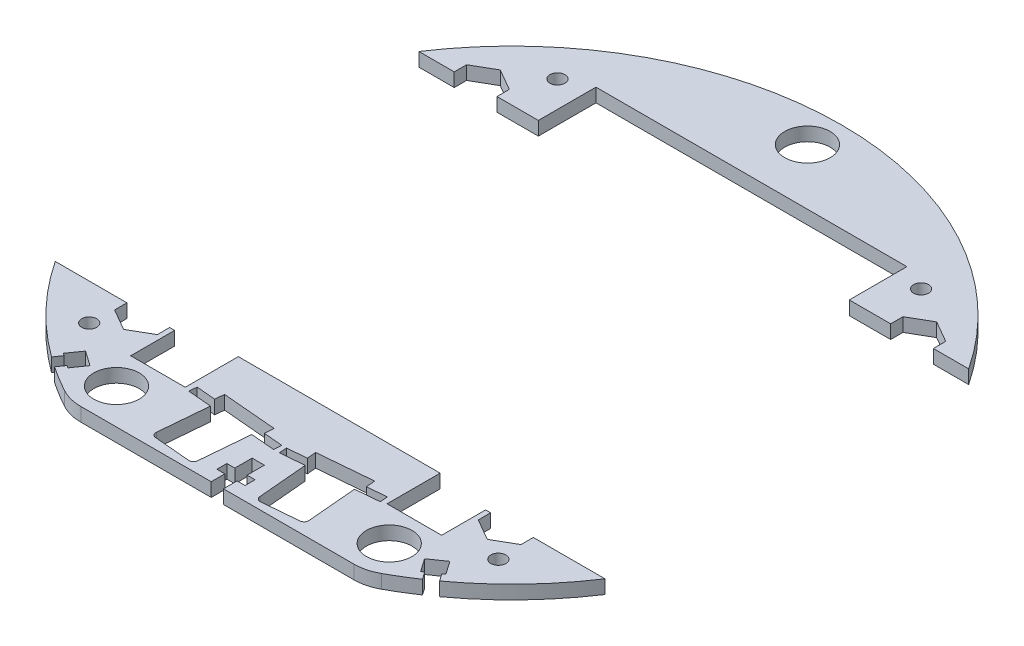
SolidWorks part; units mm, degrees
ref_plane "Front Plane" through (0, 0, 0) normal (0, 0, 1) x (1, 0, 0)
ref_plane "Top Plane" through (0, 0, 0) normal (0, 1, 0) x (1, 0, 0)
ref_plane "Right Plane" through (0, 0, 0) normal (1, 0, 0) x (0, 0, -1)
sketch "Sketch1" plane through (0, 0, 0) normal (0, 1, 0) x (1, 0, 0)
  line L0 (-30.03, -64.8129) -> (30.03, -64.8129)
  line L1 (0, -85) -> (0, 0) construction
  line L2 (0, -85) -> (32.4891, -64.8129) construction
  arc A0 (34.8348, -63.5829) -> (-34.8348, -63.5829) centre (0, 0) ccw
  circle A1 centre (0, -85) radius 38.25 construction
  arc A2 (30.03, -64.8129) -> (34.8348, -63.5829) centre (30.03, -54.8129) ccw
  arc A3 (-30.03, -64.8129) -> (-34.8348, -63.5829) centre (-30.03, -54.8129) cw
  dimension "D1" = 145
  dimension "D2" = 76.5
  dimension "D4" = 10
  dimension "D3" = 85
extrude "Boss-Extrude1" add sketch "Sketch1" along normal blind 3
sketch "Sketch2" plane through (0, 3, 0) normal (0, 1, 0) x (1, 0, 0)
  line L29 (-22.2, -49.6757) -> (-22.2, -32.5) construction
  line L30 (-22.2, -49.6757) -> (-22.2, -32.5) construction
  line L38 (-34.2, -49.6757) -> (-22.2, -49.6757) construction
  line L39 (-34.2, -49.6757) -> (-34.2, 49.6757) construction
  line L40 (-34.2, 49.6757) -> (-22.2, 49.6757) construction
  line L41 (-22.2, 32.5) -> (-22.2, 49.6757) construction
  line L47 (22.2, 32.5) -> (22.2, 49.6757) construction
  line L48 (34.2, 49.6757) -> (22.2, 49.6757) construction
  line L49 (34.2, -49.6757) -> (34.2, 49.6757) construction
  line L50 (34.2, -49.6757) -> (22.2, -49.6757) construction
  line L51 (22.2, -49.6757) -> (22.2, -32.5) construction
  line L52 (22.2, -49.6757) -> (22.2, -32.5) construction
  line L53 (-22.2, -49.6757) -> (-22.2, -38) construction
  line L54 (-22.2, -49.6757) -> (-22.2, -38)
  line L55 (-22.2, 44) -> (22.2, 44)
  line L62 (-34.2, -49.6757) -> (-22.2, -49.6757)
  line L63 (-34.2, -49.6757) -> (-34.2, 49.6757)
  line L64 (-34.2, 49.6757) -> (-22.2, 49.6757)
  line L65 (-22.2, 44) -> (-22.2, 49.6757)
  line L71 (22.2, 44) -> (22.2, 49.6757)
  line L72 (34.2, 49.6757) -> (22.2, 49.6757)
  line L73 (34.2, -49.6757) -> (34.2, 49.6757)
  line L74 (34.2, -49.6757) -> (22.2, -49.6757)
  line L75 (22.2, -49.6757) -> (22.2, -38) construction
  line L76 (22.2, -49.6757) -> (22.2, -38)
  line L77 (-22.2, -38) -> (22.2, -38)
  dimension "D1" = 38
  dimension "D2" = 44
extrude "Cut-Extrude1" cut sketch "Sketch2" against normal through all
sketch "Sketch3" plane through (0, 3, 0) normal (0, 1, 0) x (1, 0, 0)
  line L0 (-34.2, 40) -> (-34.2, -40)
  line L1 (-72.5, -40) -> (-34.2, -40)
  line L2 (-72.5, -40) -> (-72.5, 40)
  line L3 (-72.5, 40) -> (-34.2, 40)
  line L4 (72.5, -40) -> (72.5, 40)
  line L5 (-72.5, -40) -> (72.5, 40) construction
  line L6 (-72.5, 40) -> (72.5, -40) construction
  line L8 (34.2, 40) -> (34.2, -40)
  line L10 (34.2, 40) -> (72.5, 40)
  line L11 (34.2, -40) -> (72.5, -40)
  line L12 (-34.2, -49.6757) -> (-34.2, 49.6757) construction
  line L13 (34.2, -49.6757) -> (34.2, 49.6757) construction
  arc A0 (34.8348, -63.5829) -> (-34.8348, -63.5829) centre (0, 0) ccw construction
  point P0 (0, 0)
  dimension "D1" = 80
extrude "Cut-Extrude2" cut sketch "Sketch3" against normal through all
sketch "Sketch4" plane through (0, 3, 0) normal (0, 1, 0) x (1, 0, 0)
  line L0 (-21.0702, -50.0262) -> (-0.6482, -51.8129)
  line L1 (21.0702, -50.0262) -> (20.922, -48.3326)
  line L2 (0.6482, -51.8129) -> (0.5, -50.1193)
  line L3 (20.922, -48.3326) -> (0.5, -50.1193)
  line L4 (0, 0) -> (0, -64.8129) construction
  line L5 (-30.03, -64.8129) -> (30.03, -64.8129) construction
  line L6 (-20.922, -48.3326) -> (-0.5, -50.1193)
  line L7 (-0.6482, -51.8129) -> (-0.5, -50.1193)
  line L8 (-21.0702, -50.0262) -> (-20.922, -48.3326)
  line L14 (21.0702, -50.0262) -> (0.6482, -51.8129)
  dimension "D1" = 1.7
  dimension "D2" = 20.5
  dimension "D3" = 5
  dimension "D4" = 13
  dimension "D5" = 0.5
extrude "Cut-Extrude3" cut sketch "Sketch4" against normal through all
sketch "Sketch5" plane through (0, 3, 0) normal (0, 1, 0) x (1, 0, 0)
  line L0 (5.8782, -51.3553) -> (15.8401, -50.4837)
  line L1 (5.8782, -51.3553) -> (6.8369, -62.3134)
  line L2 (15.8401, -50.4837) -> (16.7988, -61.4419)
  line L3 (7.9203, -63.2225) -> (15.8898, -62.5252)
  line L4 (0.6482, -51.8129) -> (21.0702, -50.0262) construction
  line L5 (16.6882, -48.7031) -> (4.7338, -49.7489)
  line L6 (16.6882, -48.7031) -> (16.5139, -46.7107)
  line L7 (4.7338, -49.7489) -> (4.5595, -47.7565)
  line L8 (16.5139, -46.7107) -> (4.5595, -47.7565)
  line L9 (20.922, -48.3326) -> (0.5, -50.1193) construction
  line L10 (0, -38) -> (0, -64.8129) construction
  line L12 (-30.03, -64.8129) -> (30.03, -64.8129) construction
  line L13 (-16.5139, -46.7107) -> (-4.5595, -47.7565)
  line L14 (-4.7338, -49.7489) -> (-4.5595, -47.7565)
  line L15 (-16.6882, -48.7031) -> (-16.5139, -46.7107)
  line L16 (-16.6882, -48.7031) -> (-4.7338, -49.7489)
  line L17 (-7.9203, -63.2225) -> (-15.8898, -62.5252)
  line L18 (-15.8401, -50.4837) -> (-16.7988, -61.4419)
  line L19 (-5.8782, -51.3553) -> (-6.8369, -62.3134)
  line L20 (-5.8782, -51.3553) -> (-15.8401, -50.4837)
  line L21 (-22.2, -38) -> (22.2, -38) construction
  arc A0 (16.7988, -61.4419) -> (15.8898, -62.5252) centre (15.8027, -61.529) cw
  arc A1 (6.8369, -62.3134) -> (7.9203, -63.2225) centre (7.8331, -62.2263) ccw
  arc A2 (-6.8369, -62.3134) -> (-7.9203, -63.2225) centre (-7.8331, -62.2263) cw
  arc A3 (-16.7988, -61.4419) -> (-15.8898, -62.5252) centre (-15.8027, -61.529) ccw
  point P14 (10.711, -49.226)
  point P15 (10.711, -49.226)
  point P17 (10.8592, -50.9195)
  point P18 (10.8592, -50.9195)
  point P21 (16.886, -62.4381)
  point P24 (6.9241, -63.3096)
  point P40 (-6.9241, -63.3096)
  point P41 (-16.886, -62.4381)
  dimension "D5" = 1
  dimension "D1" = 12
  dimension "D2" = 10
  dimension "D3" = 12
  dimension "D4" = 2
extrude "Cut-Extrude4" cut sketch "Sketch5" against normal through all
sketch "Sketch6" plane through (0, 3, 0) normal (0, 1, 0) x (1, 0, 0)
  line L2 (-34.2, 49.6757) -> (34.2, 49.6757)
  line L3 (-34.2, 49.6757) -> (-34.2, 52.6757)
  line L4 (-34.2, 52.6757) -> (34.2, 52.6757)
  line L5 (34.2, 49.6757) -> (34.2, 52.6757)
  point P4 (34.2, 49.6757)
  dimension "D1" = 3
extrude "Cut-Extrude5" cut sketch "Sketch6" against normal through all
sketch "Sketch7" plane through (0, 3, 0) normal (0, 1, 0) x (1, 0, 0)
  circle A1 centre (-30, -57) radius 5
  circle A2 centre (-30, -57) radius 5
  circle A3 centre (30, -57) radius 5
  circle A4 centre (30, -57) radius 5
  dimension "D1" = 0
  dimension "D2" = 0
extrude "Cut-Extrude6" cut sketch "Sketch7" against normal through all
sketch "Sketch8" plane through (0, 3, 0) normal (0, 1, 0) x (1, 0, 0)
  line L10 (-52.7, 37.2865) -> (-52.7, 32.5)
  line L11 (-52.7, 32.5) -> (-43.3, 32.5)
  line L12 (-43.3, 32.5) -> (-43.3, 37.2865)
  line L13 (-43.3, 37.2865) -> (-43.3, 42.7135)
  line L14 (-43.3, 42.7135) -> (-48, 45.4271)
  line L15 (-48, 45.4271) -> (-52.7, 42.7135)
  line L16 (-52.7, 42.7135) -> (-52.7, 37.2865)
  line L17 (-52.7, 37.2865) -> (-52.7, 32.5)
  line L18 (-52.7, 32.5) -> (-43.3, 32.5)
  line L19 (-43.3, 32.5) -> (-43.3, 37.2865)
  line L20 (-43.3, 37.2865) -> (-43.3, 42.7135)
  line L21 (-43.3, 42.7135) -> (-48, 45.4271)
  line L22 (-48, 45.4271) -> (-52.7, 42.7135)
  line L23 (-52.7, 42.7135) -> (-52.7, 37.2865)
  line L24 (44.7, -32.5) -> (35.3, -32.5)
  line L25 (44.7, -37.2865) -> (44.7, -32.5)
  line L26 (44.7, -42.7135) -> (44.7, -37.2865)
  line L31 (40, -45.4271) -> (44.7, -42.7135)
  line L32 (35.3, -42.7135) -> (40, -45.4271)
  line L33 (35.3, -37.2865) -> (35.3, -42.7135)
  line L34 (35.3, -32.5) -> (35.3, -37.2865)
  line L35 (44.7, -32.5) -> (35.3, -32.5)
  line L36 (44.7, -37.2865) -> (44.7, -32.5)
  line L37 (44.7, -42.7135) -> (44.7, -37.2865)
  line L38 (40, -45.4271) -> (44.7, -42.7135)
  line L39 (35.3, -42.7135) -> (40, -45.4271)
  line L40 (35.3, -37.2865) -> (35.3, -42.7135)
  line L41 (35.3, -32.5) -> (35.3, -37.2865)
  line L42 (-35.3, -37.2865) -> (-35.3, -32.5)
  line L43 (-35.3, -32.5) -> (-44.7, -32.5)
  line L44 (-44.7, -32.5) -> (-44.7, -37.2865)
  line L45 (-44.7, -37.2865) -> (-44.7, -42.7135)
  line L46 (-44.7, -42.7135) -> (-40, -45.4271)
  line L47 (-40, -45.4271) -> (-35.3, -42.7135)
  line L48 (-35.3, -42.7135) -> (-35.3, -37.2865)
  line L49 (-35.3, -37.2865) -> (-35.3, -32.5)
  line L50 (-35.3, -32.5) -> (-44.7, -32.5)
  line L51 (-44.7, -32.5) -> (-44.7, -37.2865)
  line L52 (-44.7, -37.2865) -> (-44.7, -42.7135)
  line L53 (-44.7, -42.7135) -> (-40, -45.4271)
  line L54 (-40, -45.4271) -> (-35.3, -42.7135)
  line L55 (-35.3, -42.7135) -> (-35.3, -37.2865)
  line L56 (52.7, 32.5) -> (52.7, 37.2865)
  line L57 (52.7, 37.2865) -> (52.7, 42.7135)
  line L58 (52.7, 42.7135) -> (48, 45.4271)
  line L59 (48, 45.4271) -> (43.3, 42.7135)
  line L60 (43.3, 42.7135) -> (43.3, 37.2865)
  line L61 (43.3, 37.2865) -> (43.3, 32.5)
  line L62 (43.3, 32.5) -> (52.7, 32.5)
  line L63 (52.7, 32.5) -> (52.7, 37.2865)
  line L64 (52.7, 37.2865) -> (52.7, 42.7135)
  line L65 (52.7, 42.7135) -> (48, 45.4271)
  line L66 (48, 45.4271) -> (43.3, 42.7135)
  line L67 (43.3, 42.7135) -> (43.3, 37.2865)
  line L68 (43.3, 37.2865) -> (43.3, 32.5)
  line L69 (43.3, 32.5) -> (52.7, 32.5)
  dimension "D1" = 0
  dimension "D2" = 0
  dimension "D3" = 0
  dimension "D4" = 0
extrude "Cut-Extrude7" cut sketch "Sketch8" against normal through all
sketch "Sketch11" plane through (0, 3, 0) normal (0, 1, 0) x (1, 0, 0)
  line L0 (0, 0) -> (0, 65) construction
  circle A0 centre (0, 65) radius 5
  dimension "D2" = 10
  dimension "D1" = 65
extrude "Cut-Extrude10" cut sketch "Sketch11" against normal through all
sketch "Sketch12" plane through (0, 3, 0) normal (0, 1, 0) x (1, 0, 0)
  line L0 (-30.03, -64.8129) -> (30.03, -64.8129) construction
  line L1 (-1.35, -64.8129) -> (1.35, -64.8129)
  line L2 (-1.35, -64.8129) -> (-1.35, -61.8129)
  line L3 (-1.35, -55.8129) -> (1.35, -55.8129)
  line L4 (1.35, -64.8129) -> (1.35, -61.8129)
  line L5 (-1.35, -59.6129) -> (-3.1, -59.6129)
  line L6 (3.1, -59.6129) -> (1.35, -59.6129)
  line L7 (3.1, -59.6129) -> (3.1, -61.8129)
  line L8 (3.1, -61.8129) -> (1.35, -61.8129)
  line L9 (-3.1, -59.6129) -> (-3.1, -61.8129)
  line L10 (-1.35, -61.8129) -> (-3.1, -61.8129)
  line L11 (-1.35, -59.6129) -> (-1.35, -55.8129)
  line L12 (1.35, -59.6129) -> (1.35, -55.8129)
  point P14 (0, -64.8129)
  point P15 (0, -64.8129)
  dimension "D1" = 3
  dimension "D2" = 9
  dimension "D3" = 2.7
  dimension "D4" = 2.2
  dimension "D5" = 6.2
extrude "Cut-Extrude11" cut sketch "Sketch12" against normal through all
sketch "Sketch13" plane through (0, 3, 0) normal (0, 1, 0) x (1, 0, 0)
  line L0 (0, 0) -> (0, -22.8942) construction
  circle A0 centre (45, -48) radius 1.65
  circle A1 centre (-45, -48) radius 1.65
  circle A2 centre (40, 50) radius 1.65
  circle A3 centre (-40, 50) radius 1.65
  dimension "D3" = 3.3
  dimension "D1" = 48
  dimension "D2" = 45
  dimension "D4" = 40
  dimension "D5" = 50
extrude "Cut-Extrude12" cut sketch "Sketch13" against normal through all
sketch "Sketch14" plane through (0, 0, 0) normal (0, -1, 0) x (1, 0, 0)
  line L8 (-41.543, 56.9759) -> (-42.0754, 56.6031)
  line L9 (-42.0754, 56.6031) -> (-40.0679, 53.736)
  line L10 (-40.0679, 53.736) -> (-36.7913, 56.0303)
  line L11 (-36.7913, 56.0303) -> (-38.7988, 58.8974)
  line L12 (-38.7988, 58.8974) -> (-39.3313, 58.5245)
  line L13 (-39.3313, 58.5245) -> (-40.4784, 60.1629)
  line L14 (-40.4784, 60.1629) -> (-42.6901, 58.6142)
  line L15 (-42.6901, 58.6142) -> (-41.543, 56.9759)
  line L16 (-41.543, 56.9759) -> (-42.0754, 56.6031)
  line L17 (-42.0754, 56.6031) -> (-40.0679, 53.736)
  line L18 (-40.0679, 53.736) -> (-36.7913, 56.0303)
  line L19 (-36.7913, 56.0303) -> (-38.7988, 58.8974)
  line L20 (-38.7988, 58.8974) -> (-39.3313, 58.5245)
  line L21 (-39.3313, 58.5245) -> (-40.4784, 60.1629)
  line L22 (-40.4784, 60.1629) -> (-42.6901, 58.6142)
  line L23 (-42.6901, 58.6142) -> (-41.543, 56.9759)
  line L24 (41.543, 56.9759) -> (42.6901, 58.6142)
  line L25 (42.0754, 56.6031) -> (41.543, 56.9759)
  line L26 (40.0679, 53.736) -> (42.0754, 56.6031)
  line L27 (36.7913, 56.0303) -> (40.0679, 53.736)
  line L28 (38.7988, 58.8974) -> (36.7913, 56.0303)
  line L29 (39.3313, 58.5245) -> (38.7988, 58.8974)
  line L30 (40.4784, 60.1629) -> (39.3313, 58.5245)
  line L31 (42.6901, 58.6142) -> (40.4784, 60.1629)
  line L32 (41.543, 56.9759) -> (42.6901, 58.6142)
  line L33 (42.0754, 56.6031) -> (41.543, 56.9759)
  line L34 (40.0679, 53.736) -> (42.0754, 56.6031)
  line L35 (36.7913, 56.0303) -> (40.0679, 53.736)
  line L36 (38.7988, 58.8974) -> (36.7913, 56.0303)
  line L37 (39.3313, 58.5245) -> (38.7988, 58.8974)
  line L38 (40.4784, 60.1629) -> (39.3313, 58.5245)
  line L39 (42.6901, 58.6142) -> (40.4784, 60.1629)
  dimension "D1" = 0
  dimension "D2" = 0
extrude "Cut-Extrude13" cut sketch "Sketch14" against normal through all
equation "\"smallPulleyTeeth\"= 30"
equation "\"largePulleyTeeth\"= 30"
equation "\"eighthThick\"= 3.0mm"
equation "\"sixteenthThick\" = 1.7mm"
equation "\"quarterThick\"=6.0mm"
equation "\"OD\" = 145mm"
equation "\"puckAngle\" = 60.5deg"
equation "\"puckDiam\" = 76.5mm"
equation "\"axlePress\" = 5.9mm"
equation "\"press\" = 0.2mm"
equation "\"wheelClear\" = 0.3mm"
equation "\"10-32clear\" = 4.8mm"
equation "\"6-32clear\" = 3.3mm"
equation "\"8-32clear\" = 4.0mm"
equation "\"4-40clear\" = 3.0mm"
equation "\"wheelHeight\" = 22mm"
equation "\"wheelWell\" = 65mm"
equation "\"D1@Sketch1\"=\"OD\""
equation "\"D1@Boss-Extrude1\"=\"eighthThick\""
equation "\"D2@Sketch1\"=\"puckDiam\""
equation "\"puckDist\" = 85mm"
equation "\"scoopFillet\" = 5mm"
equation "\"10-32tap\" = 4.45mm"
equation "\"ledSmall\" = 3.1mm"
equation "\"ledLarge\" = 4.2mm"
equation "\"ledLength\" = 4.2mm"
equation "\"D3@Sketch1\"=\"puckDist\""
equation "\"4-40close\" = 2.7mm"
equation "\"4-40nutThick\" = 2.2mm"
equation "\"4-40nutWidth\" = 6.2mm"
equation "\"D3@Sketch12\"=\"4-40close\""
equation "\"D4@Sketch12\"=\"4-40nutThick\""
equation "\"D5@Sketch12\"=\"4-40nutWidth\""
equation "\"D3@Sketch13\"=\"6-32clear\""
equation "\"D1@Sketch6\"=\"eighthThick\""
